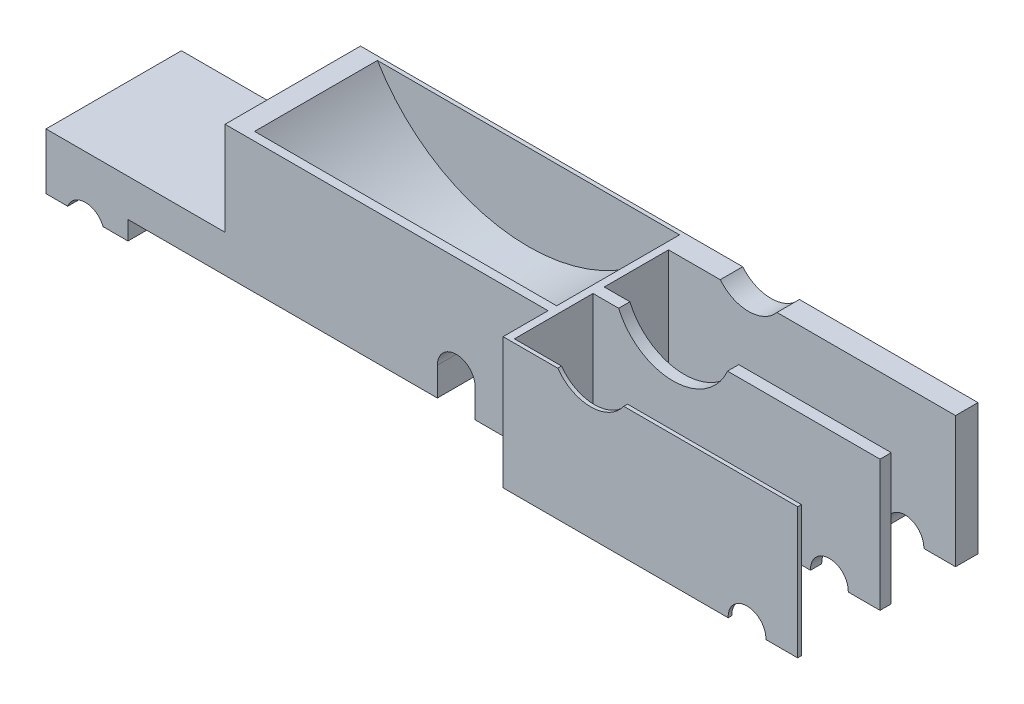
SolidWorks part; units mm, degrees
ref_plane "Front Plane" through (0, 0, 0) normal (0, 0, 1) x (1, 0, 0)
ref_plane "Top Plane" through (0, 0, 0) normal (0, 1, 0) x (1, 0, 0)
ref_plane "Right Plane" through (0, 0, 0) normal (1, 0, 0) x (0, 0, -1)
sketch "Sketch1" plane through (0, 0, 0) normal (0, 1, 0) x (1, 0, 0)
  line L1 (0, 0) -> (419.1, 0)
  line L2 (0, 0) -> (0, 142.1841)
  line L3 (0, 142.1841) -> (419.1, 142.1841)
  line L4 (419.1, 0) -> (419.1, 142.1841)
  dimension "D1" = 419.1
  dimension "D2" = 142.1841
extrude "Boss-Extrude1" add sketch "Sketch1" along normal blind 88.9
ref_plane "Plane1" through (0, 0, -134.333) normal (0, 0, -1) x (-1, 0, 0)
ref_plane "Plane2" through (0, 0, -67.8332) normal (0, 0, -1) x (-1, 0, 0)
ref_plane "Plane3" through (0, 0, -14.4831) normal (0, 0, -1) x (-1, 0, 0)
ref_plane "Plane4" through (0, 0, -131.633) normal (0, 0, -1) x (-1, 0, 0)
sketch "Sketch2" plane through (0, 0, -131.633) normal (0, 0, -1) x (-1, 0, 0)
  circle A0 centre (-116.7166, 150.0612) radius 119.38
  arc A1 (-20.1165, 209.6486) -> (-213.3168, 90.4738) centre (-116.7166, 150.0612) ccw construction
  dimension "D1" = 238.76
sketch "Sketch3" plane through (0, 0, -134.333) normal (0, 0, -1) x (-1, 0, 0)
  line L0 (-116.7166, 150.0612) -> (-278.6494, 104.852) construction
  circle A0 centre (-278.6494, 104.852) radius 24.9999
sketch "Sketch4" plane through (0, 0, -67.8332) normal (0, 0, -1) x (-1, 0, 0)
  circle A0 centre (-278.6494, 104.852) radius 40.2501
  dimension "D1" = 80.5002
sketch "Sketch5" plane through (0, 0, -14.4831) normal (0, 0, -1) x (-1, 0, 0)
  circle A0 centre (-278.6494, 104.852) radius 27.5006
  dimension "D1" = 55.0012
sketch "Sketch6" plane through (0, 88.9, 0) normal (0, 1, 0) x (1, 0, 0)
  line L0 (278.6494, 14.4831) -> (278.6494, 11.9431) construction
  line L1 (306.1499, 14.4831) -> (251.1488, 14.4831) construction
  line L2 (278.6494, 67.8332) -> (278.6494, 60.2336) construction
  line L3 (318.8995, 67.8332) -> (238.3992, 67.8332) construction
  line L4 (278.6494, 134.333) -> (278.6494, 119.093) construction
  line L5 (303.6493, 134.333) -> (253.6494, 134.333) construction
  dimension "D1" = 2.54
  dimension "D2" = 7.5997
  dimension "D3" = 15.24
extrude "Cut-Extrude1" cut sketch "Sketch2" against normal blind 83.4009
sketch "Sketch7" plane through (0, 88.9, 0) normal (0, 1, 0) x (1, 0, 0)
  line L0 (419.1, 0) -> (419.1, 142.1841) construction
  line L1 (419.1, 119.093) -> (224.3193, 119.093)
  line L2 (419.1, 119.093) -> (419.1, 75.4532)
  line L3 (419.1, 67.8332) -> (224.3193, 67.8332)
  line L4 (224.3193, 119.093) -> (224.3193, 75.4532)
  line L5 (318.8995, 67.8332) -> (238.3992, 67.8332) construction
  line L6 (48.895, 14.4831) -> (-48.895, 14.4831) construction
  line L8 (224.3193, 67.8332) -> (224.3193, 14.4831)
  line L9 (224.3193, 14.4831) -> (419.1, 14.4831)
  line L10 (419.1, 67.8332) -> (419.1, 14.4831)
  line L11 (219.2393, 131.633) -> (219.2393, 48.2321) construction
  line L12 (224.3193, 75.4532) -> (419.1, 75.4532)
  dimension "D1" = 5.08
  dimension "D2" = 7.62
extrude "Cut-Extrude2" cut sketch "Sketch7" against normal through all
extrude "Cut-Extrude3" cut sketch "Sketch3" against normal up to vertex (15.24 mm away) up to point (278.6494, 88.9, -119.093)
extrude "Cut-Extrude4" cut sketch "Sketch4" along normal blind 10
extrude "Cut-Extrude5" cut sketch "Sketch5" against normal up to vertex (2.54 mm away) up to point (278.6494, 88.9, -11.9431)
sketch "Sketch8" plane through (0, 0, -142.1841) normal (0, 0, -1) x (-1, 0, 0)
  line L1 (-419.1, 88.9) -> (0, 88.9)
  line L2 (-419.1, 88.9) -> (-419.1, 0)
  line L3 (-419.1, 0) -> (0, 0)
  line L4 (0, 88.9) -> (0, 0)
extrude "Cut-Extrude6" cut sketch "Sketch8" against normal up to vertex (7.8511 mm away) up to point (278.6494, 88.9, -134.333)
sketch "Sketch9" plane through (0, 0, 0) normal (0, 0, 1) x (1, 0, 0)
  line L1 (0, 88.9) -> (419.1, 88.9)
  line L2 (0, 88.9) -> (0, 0)
  line L3 (0, 0) -> (419.1, 0)
  line L4 (419.1, 88.9) -> (419.1, 0)
extrude "Cut-Extrude7" cut sketch "Sketch9" against normal up to vertex (11.9431 mm away) up to point (278.6494, 88.9, -11.9431)
sketch "Sketch10" plane through (0, 0, -11.9431) normal (0, 0, 1) x (1, 0, 0)
  line L0 (0, 0) -> (419.1, 0) construction
  line L1 (0, 88.9) -> (219.202, 88.9)
  line L2 (0, 88.9) -> (0, 0)
  line L3 (0, 0) -> (219.202, 0)
  line L4 (219.202, 88.9) -> (219.202, 0)
  dimension "D1" = 219.202
extrude "Cut-Extrude8" cut sketch "Sketch10" against normal blind 30.48
sketch "Sketch12" plane through (0, 0, 0) normal (0, -1, 0) x (1, 0, 0)
  line L5 (0, -42.4231) -> (-121.5336, -42.4231)
  line L6 (0, -42.4231) -> (0, -134.333)
  line L7 (0, -134.333) -> (-121.5336, -134.333)
  line L8 (-121.5336, -42.4231) -> (-121.5336, -134.333)
  line L9 (0, -88.378) -> (53.0931, -88.378) construction
  line L10 (0, -134.333) -> (0, -42.4231) construction
  line L11 (0, -42.4231) -> (219.202, -42.4231) construction
  point P9 (0, -88.378)
  dimension "D1" = 121.5336
extrude "Boss-Extrude2" add sketch "Sketch12" against normal blind 25.4
sketch "Sketch14" plane through (0, 0, 0) normal (0, -1, 0) x (1, 0, 0)
  line L0 (419.1, -134.333) -> (-121.5336, -134.333) construction
  line L1 (-121.5336, -42.4231) -> (-65.8865, -42.4231)
  line L2 (-121.5336, -42.4231) -> (-121.5336, -134.333)
  line L3 (-121.5336, -134.333) -> (-65.8865, -134.333)
  line L4 (-65.8865, -42.4231) -> (-65.8865, -134.333)
extrude "Boss-Extrude3" add sketch "Sketch14" along normal blind 12.7
sketch "Sketch17" plane through (0, 0, -134.333) normal (0, 0, -1) x (-1, 0, 0)
  line L0 (-169.736, 19.3164) -> (-169.736, 0)
  line L1 (-419.1, 0) -> (65.8865, 0) construction
  line L2 (-169.736, 0) -> (-144.082, 0)
  line L3 (-144.082, 0) -> (-144.082, 19.3164)
  circle A0 centre (-384.7359, 0.5319) radius 12.827
  arc A1 (-144.082, 19.3164) -> (-169.736, 19.3164) centre (-156.909, 19.3164) ccw
  circle A2 centre (94.7989, -17.274) radius 12.827
  dimension "D1" = 25.654
  dimension "D2" = 25.654
  dimension "D3" = 25.654
extrude "Cut-Extrude10" cut sketch "Sketch17" against normal through all
